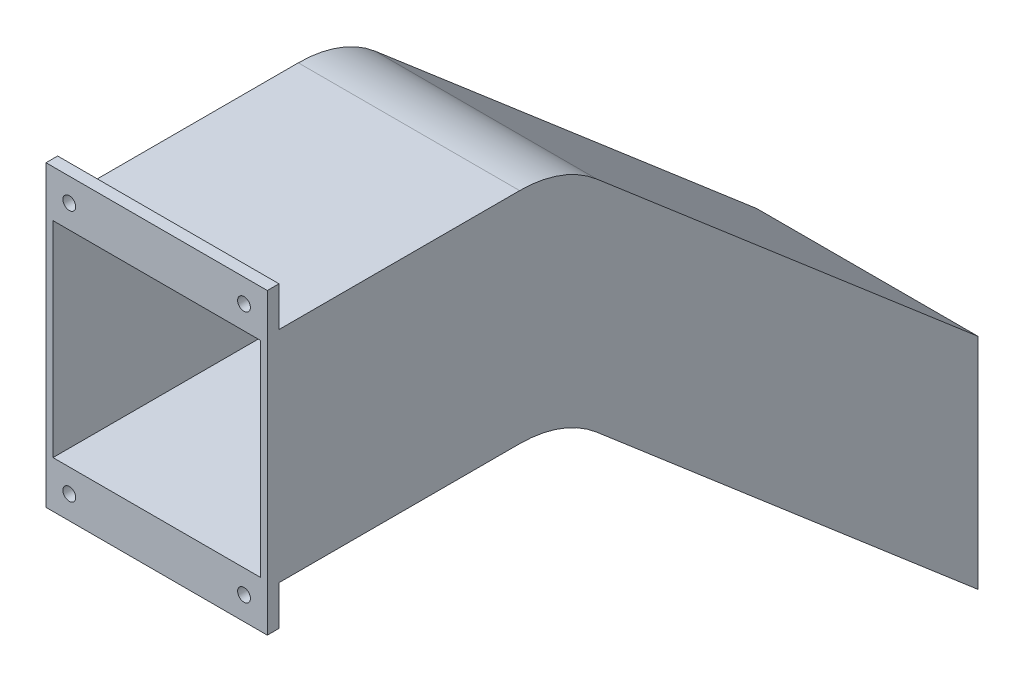
SolidWorks part; units mm, degrees
ref_plane "Front Plane" through (0, 0, 0) normal (0, 0, 1) x (1, 0, 0)
ref_plane "Top Plane" through (0, 0, 0) normal (0, 1, 0) x (1, 0, 0)
ref_plane "Right Plane" through (0, 0, 0) normal (1, 0, 0) x (0, 0, -1)
sketch "Sketch1" plane through (0, 0, 0) normal (0, 0, 1) x (1, 0, 0)
  line L1 (-47.4625, -47.0125) -> (47.4625, -47.0125)
  line L2 (-47.4625, -47.0125) -> (-47.4625, 47.0125)
  line L3 (-47.4625, 47.0125) -> (47.4625, 47.0125)
  line L4 (47.4625, -47.0125) -> (47.4625, 47.0125)
  line L5 (-47.4625, -47.0125) -> (47.4625, 47.0125) construction
  line L6 (-47.4625, 47.0125) -> (47.4625, -47.0125) construction
  point P0 (0, 0)
  dimension "D1" = 94.025
  dimension "D2" = 94.925
extrude "Boss-Extrude1" add sketch "Sketch1" along normal blind 127
sketch "Sketch2" plane through (47.4625, 0, 0) normal (1, 0, 0) x (0, 0, -1)
  line L0 (0, -47.0125) -> (177.8, -199.4125)
  line L1 (177.8, -199.4125) -> (177.8, -105.3875)
  line L2 (177.8, -105.3875) -> (0, 47.0125)
  line L3 (0, 47.0125) -> (0, -47.0125)
  line L4 (0, -47.0125) -> (0, -199.4125) construction
  line L5 (0, -199.4125) -> (177.8, -199.4125) construction
  dimension "D1" = 177.8
  dimension "D2" = 152.4
extrude "Boss-Extrude2" add sketch "Sketch2" against normal up to surface (94.925 mm away) up to face at (-47.4625, 0, 63.5)
fillet "Fillet1" radius 50.8 2 edges at (0, 47.0125, 0) (0, -47.0125, 0)
shell "Shell1" thickness 3
sketch "Sketch3" plane through (0, -47.0125, 0) normal (0, -1, 0) x (-1, 0, 0)
  line L0 (-47.4625, -127) -> (-47.4625, -18.7921) construction
  line L1 (47.4625, -127) -> (-47.4625, -127)
  line L2 (47.4625, -127) -> (47.4625, -122)
  line L3 (47.4625, -122) -> (-47.4625, -122)
  line L4 (-47.4625, -127) -> (-47.4625, -122)
  line L5 (47.4625, -127) -> (-47.4625, -122) construction
  line L6 (47.4625, -122) -> (-47.4625, -127) construction
  point P4 (0, -124.5)
  dimension "D1" = 5
extrude "Boss-Extrude3" add sketch "Sketch3" along normal blind 17
sketch "Sketch4" plane through (0, 47.0125, 0) normal (0, 1, 0) x (1, 0, 0)
  line L0 (47.4625, -127) -> (47.4625, -18.7921) construction
  line L1 (-47.4625, -127) -> (47.4625, -127)
  line L2 (-47.4625, -127) -> (-47.4625, -122)
  line L3 (-47.4625, -122) -> (47.4625, -122)
  line L4 (47.4625, -127) -> (47.4625, -122)
  line L5 (-47.4625, -127) -> (47.4625, -122) construction
  line L6 (-47.4625, -122) -> (47.4625, -127) construction
  point P4 (0, -124.5)
  dimension "D1" = 5
extrude "Boss-Extrude4" add sketch "Sketch4" along normal blind 17
sketch "Sketch5" plane through (0, 0, 122) normal (0, 0, -1) x (-1, 0, 0)
  line L0 (47.4625, 54.0125) -> (-47.4625, 54.0125) construction
  line L1 (47.4625, 64.0125) -> (47.4625, 47.0125) construction
  line L2 (-47.4625, 64.0125) -> (-47.4625, 47.0125) construction
  line L3 (47.4625, -54.0125) -> (-47.4625, -54.0125) construction
  line L4 (47.4625, -64.0125) -> (47.4625, -47.0125) construction
  line L5 (-47.4625, -64.0125) -> (-47.4625, -47.0125) construction
  line L6 (47.4625, 64.0125) -> (-47.4625, 64.0125) construction
  line L7 (47.4625, -64.0125) -> (-47.4625, -64.0125) construction
  line L8 (-47.4625, 0) -> (47.4625, 0) construction
  line L9 (-47.4625, -64.0125) -> (-47.4625, 64.0125) construction
  line L10 (47.4625, 64.0125) -> (47.4625, -64.0125) construction
  line L11 (0, 0) -> (0, 64.0125) construction
  circle A0 centre (37.4625, 54.0125) radius 2.75
  circle A1 centre (-37.4625, 54.0125) radius 2.75
  circle A2 centre (37.4625, -54.0125) radius 2.75
  circle A3 centre (-37.4625, -54.0125) radius 2.75
  dimension "D3" = 5.5
  dimension "D4" = 10
  dimension "D1" = 10
  dimension "D2" = 10
extrude "Cut-Extrude1" cut sketch "Sketch5" against normal up to next
